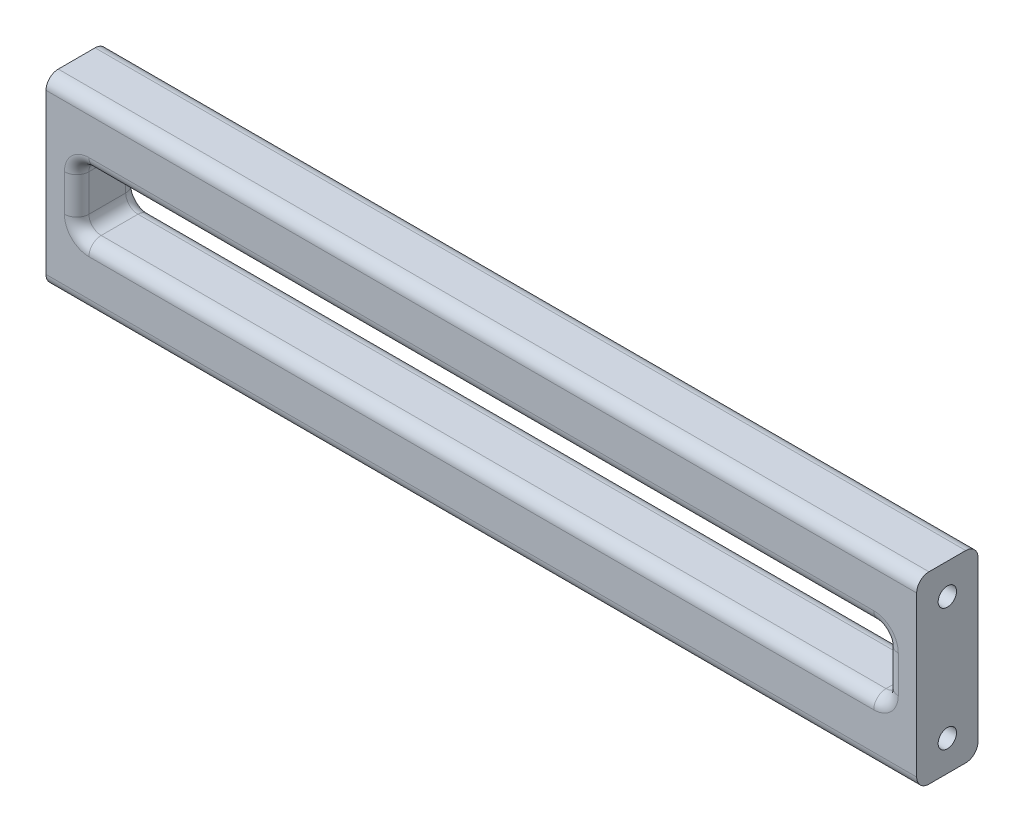
SolidWorks part; units mm, degrees
ref_plane "Front Plane" through (0, 0, 0) normal (0, 0, 1) x (1, 0, 0)
ref_plane "Top Plane" through (0, 0, 0) normal (0, 1, 0) x (1, 0, 0)
ref_plane "Right Plane" through (0, 0, 0) normal (1, 0, 0) x (0, 0, -1)
sketch "Sketch1" plane through (0, 0, 0) normal (1, 0, 0) x (0, 0, -1)
  line L1 (6.35, 19.05) -> (-6.35, 19.05)
  line L2 (6.35, 19.05) -> (6.35, -19.05)
  line L3 (6.35, -19.05) -> (-6.35, -19.05)
  line L4 (-6.35, 19.05) -> (-6.35, -19.05)
  line L5 (6.35, 19.05) -> (-6.35, -19.05) construction
  line L6 (6.35, -19.05) -> (-6.35, 19.05) construction
  circle A0 centre (0, -12.7) radius 1.905
  circle A1 centre (0, 12.7) radius 1.905
  point P0 (0, 0)
  point P10 (0, 0)
  dimension "D3" = 25.4
  dimension "D5" = 3.81
  dimension "D1" = 38.1
  dimension "D2" = 12.7
  dimension "D4" = 6.35
extrude "Boss-Extrude1" add sketch "Sketch1" against normal blind 180.34
sketch "Sketch3" plane through (0, 0, 6.35) normal (0, 0, 1) x (1, 0, 0)
  line L1 (-173.99, -6.35) -> (-6.35, -6.35)
  line L2 (-173.99, -6.35) -> (-173.99, 6.35)
  line L3 (-173.99, 6.35) -> (-6.35, 6.35)
  line L4 (-6.35, -6.35) -> (-6.35, 6.35)
  line L5 (-173.99, -6.35) -> (-6.35, 6.35) construction
  line L6 (-173.99, 6.35) -> (-6.35, -6.35) construction
  line L8 (-180.34, 19.05) -> (0, 19.05) construction
  point P0 (-90.17, 0)
  point P5 (0, 0)
  point P14 (-90.17, 19.05)
  dimension "D1" = 12.7
  dimension "D2" = 167.64
extrude "Cut-Extrude1" cut sketch "Sketch3" against normal through all
fillet "Fillet1" radius 2.54 16 edges at (-90.17, -19.05, 6.35) (-90.17, -19.05, -6.35) (-90.17, 19.05, -6.35) (-90.17, 19.05, 6.35) (-90.17, 6.35, -6.35) (-90.17, 6.35, 6.35) (-90.17, -6.35, -6.35) (-90.17, -6.35, 6.35) (-6.35, -6.35, 0) (-6.35, 0, -6.35) (-6.35, 6.35, 0) (-6.35, 0, 6.35) (-173.99, 6.35, 0) (-173.99, 0, -6.35) (-173.99, -6.35, 0) (-173.99, 0, 6.35)
